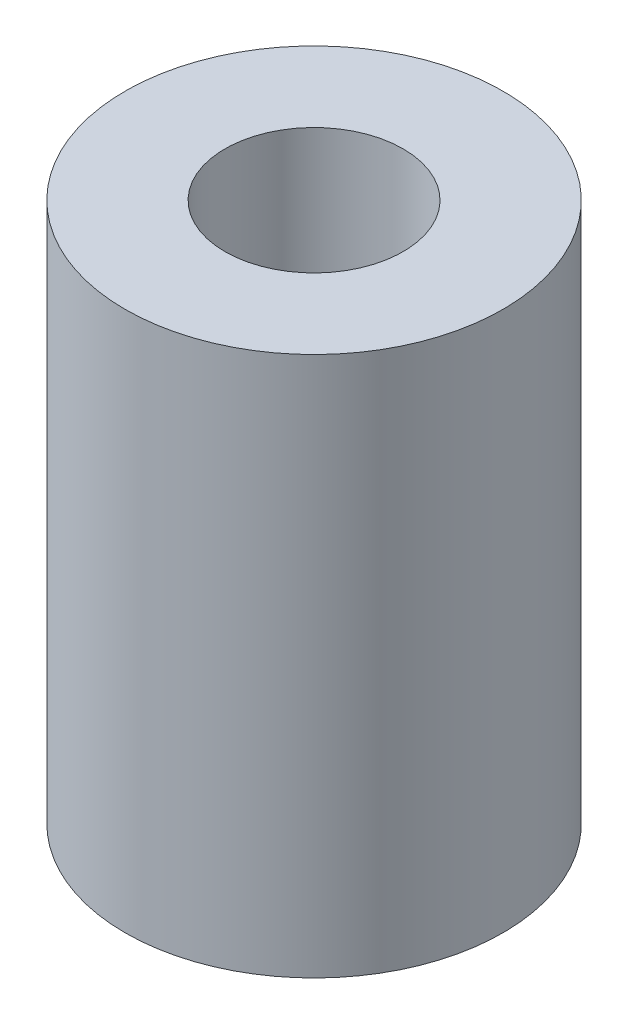
SolidWorks part; units mm, degrees
ref_plane "Front Plane" through (0, 0, 0) normal (0, 0, 1) x (1, 0, 0)
ref_plane "Top Plane" through (0, 0, 0) normal (0, 1, 0) x (1, 0, 0)
ref_plane "Right Plane" through (0, 0, 0) normal (1, 0, 0) x (0, 0, -1)
sketch "Sketch1" plane through (0, 0, 0) normal (0, 1, 0) x (1, 0, 0)
  circle A0 centre (0, 0) radius 3.5
  dimension "D1" = 7
extrude "Boss-Extrude1" add sketch "Sketch1" along normal blind 10
sketch "Sketch2" plane through (0, 10, 0) normal (0, 1, 0) x (1, 0, 0)
  circle A0 centre (0, 0) radius 1.65
  dimension "D1" = 3.3
extrude "Cut-Extrude1" cut sketch "Sketch2" against normal through all
